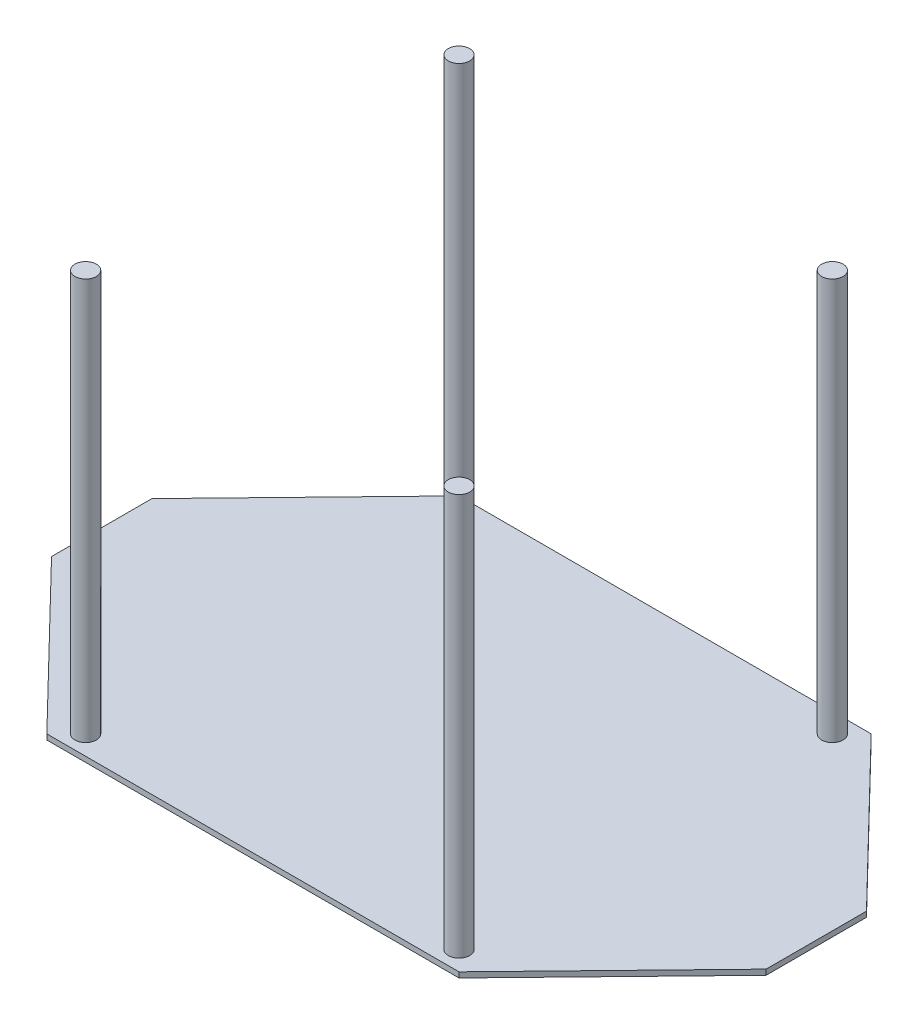
SolidWorks part; units mm, degrees
ref_plane "Спереди" through (0, 0, 0) normal (0, 0, 1) x (1, 0, 0)
ref_plane "Сверху" through (0, 0, 0) normal (0, 1, 0) x (1, 0, 0)
ref_plane "Справа" through (0, 0, 0) normal (1, 0, 0) x (0, 0, -1)
sketch "Эскиз1" plane through (0, 0, 0) normal (0, 1, 0) x (1, 0, 0)
  line L0 (-370.564, 0) -> (456.8658, 0) construction
  line L1 (154, -154) -> (-154, -154)
  line L3 (154, 154) -> (-154, 154)
  line L5 (154, -154) -> (-154, 154) construction
  line L6 (154, 154) -> (-154, -154) construction
  line L7 (0, 288.3475) -> (0, -286.7504) construction
  line L8 (-267, -37.5) -> (-267, 37.5)
  line L9 (-267, 37.5) -> (-154, 154)
  line L10 (-267, -37.5) -> (-154, -154)
  line L11 (267, -37.5) -> (154, -154)
  line L12 (267, -37.5) -> (267, 37.5)
  line L13 (267, 37.5) -> (154, 154)
  point P0 (0, 0)
  dimension "D1" = 308
  dimension "D2" = 308
  dimension "D3" = 37.5
  dimension "D4" = 75
  dimension "D5" = 267
  dimension "D6" = 154
extrude "Бобышка-Вытянуть2" add sketch "Эскиз1" against normal blind 4
sketch "Эскиз2" plane through (0, 0, 0) normal (0, 1, 0) x (1, 0, 0)
  line L0 (0, 191.6421) -> (0, -197.6084) construction
  line L5 (139.5, -139.5) -> (-139.5, 139.5) construction
  line L6 (139.5, 139.5) -> (-139.5, -139.5) construction
  line L7 (-353.5479, 0) -> (405.5152, 0) construction
  circle A0 centre (-139.5, 139.5) radius 8
  circle A1 centre (139.5, 139.5) radius 8
  circle A2 centre (139.5, -139.5) radius 8
  circle A3 centre (-139.5, -139.5) radius 8
  point P0 (0, 0)
  dimension "D3" = 16
  dimension "D1" = 279
  dimension "D2" = 279
extrude "Бобышка-Вытянуть3" add sketch "Эскиз2" along normal blind 300
